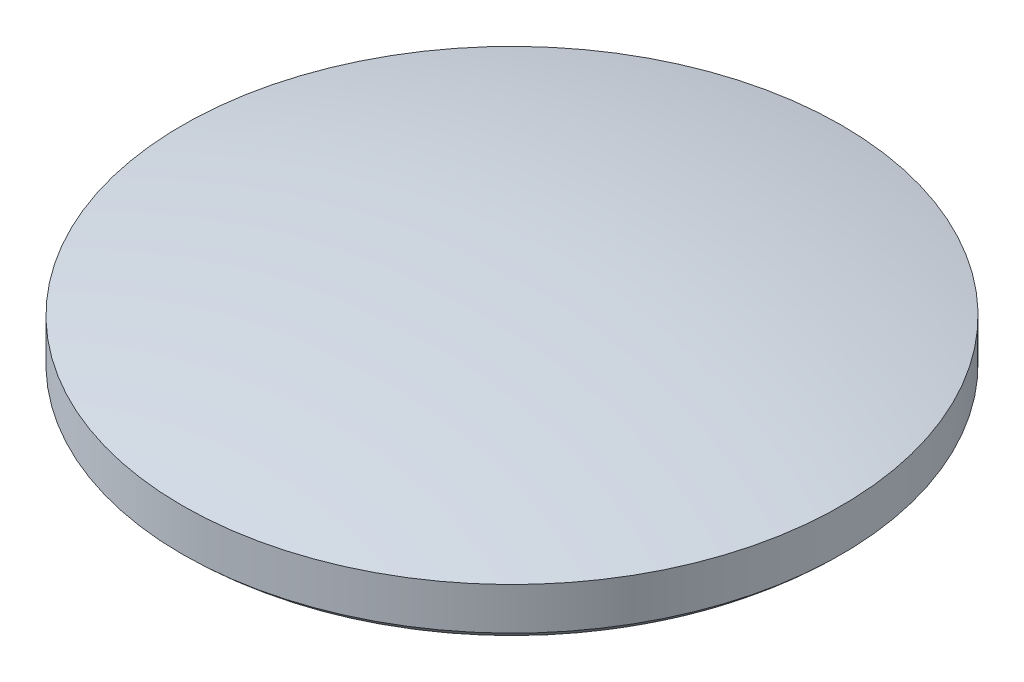
SolidWorks part; units mm, degrees
material "片状模压塑料板材"
ref_plane "前视基准面" through (0, 0, 0) normal (0, 0, 1) x (1, 0, 0)
ref_plane "上视基准面" through (0, 0, 0) normal (0, 1, 0) x (1, 0, 0)
ref_plane "右视基准面" through (0, 0, 0) normal (1, 0, 0) x (0, 0, -1)
sketch "草图1" plane through (0, 0, 0) normal (0, 0, 1) x (1, 0, 0)
  line L0 (0, 0) -> (23.4771, 0) construction
  line L1 (23.4771, 0) -> (23.4771, 3)
  line L2 (21.9824, -1.2077) -> (0, -1.2077)
  line L3 (0, -1.2077) -> (0, 5.7819)
  line L4 (0, 8.9312) -> (0, -5.8892) construction
  arc A1 (23.4771, 0) -> (21.9824, -1.2077) centre (16.5743, 7.0146) cw
  arc A2 (23.4771, 3) -> (0, 5.7819) centre (0.3241, -91.9389) ccw
revolve "旋转1" add sketch "草图1" angle 360 about L4
